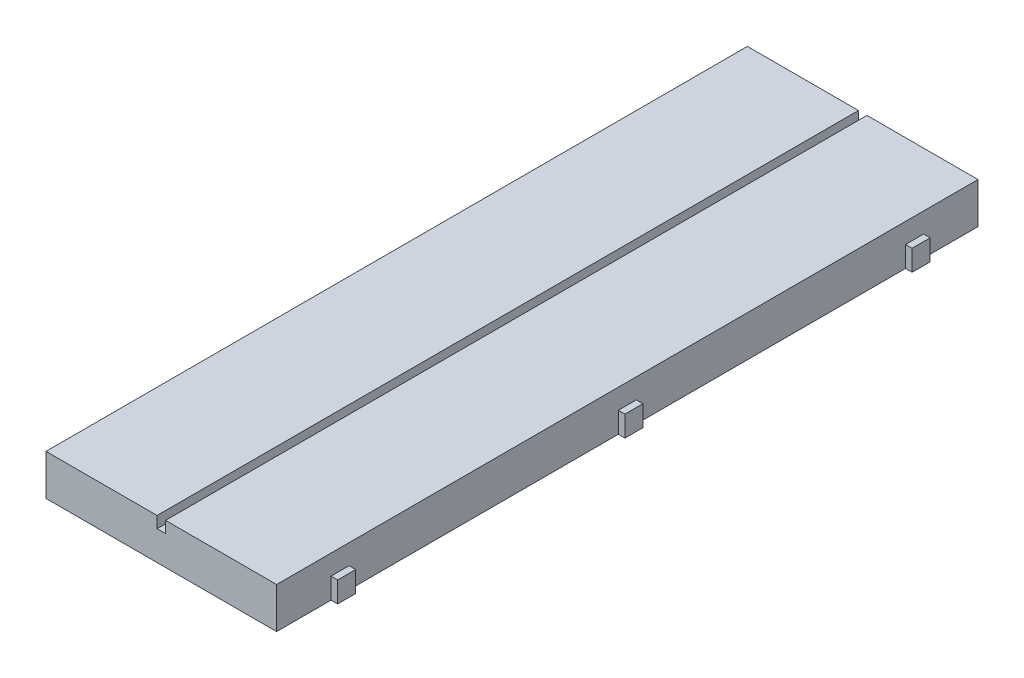
SolidWorks part; units mm, degrees
ref_plane "Front Plane" through (0, 0, 0) normal (0, 0, 1) x (1, 0, 0)
ref_plane "Top Plane" through (0, 0, 0) normal (0, 1, 0) x (1, 0, 0)
ref_plane "Right Plane" through (0, 0, 0) normal (1, 0, 0) x (0, 0, -1)
sketch "Sketch1" plane through (0, 0, 0) normal (0, 1, 0) x (1, 0, 0)
  line L1 (-27.125, -82.5) -> (27.125, -82.5)
  line L2 (-27.125, -82.5) -> (-27.125, 82.5)
  line L3 (-27.125, 82.5) -> (27.125, 82.5)
  line L4 (27.125, -82.5) -> (27.125, 82.5)
  line L5 (-27.125, -82.5) -> (27.125, 82.5) construction
  line L6 (-27.125, 82.5) -> (27.125, -82.5) construction
  point P0 (0, 0)
  dimension "D1" = 54.25
  dimension "D2" = 165
extrude "Boss-Extrude1" add sketch "Sketch1" against normal blind 9.6
sketch "Sketch2" plane through (27.125, 0, 0) normal (1, 0, 0) x (0, 0, -1)
  line L0 (82.5, -4.7) -> (69.7, -4.7)
  line L1 (82.5, -9.6) -> (82.5, 0) construction
  line L2 (-82.5, -9.6) -> (82.5, -9.6) construction
  line L3 (69.7, -4.7) -> (65.45, -4.7)
  line L4 (69.7, -4.7) -> (69.7, -9.6)
  line L5 (69.7, -9.6) -> (65.45, -9.6)
  line L6 (65.45, -4.7) -> (65.45, -9.6)
  line L7 (0, 0) -> (0, -9.6)
  line L8 (-2.125, -4.7) -> (2.125, -4.7)
  line L9 (-2.125, -4.7) -> (-2.125, -9.6)
  line L10 (-2.125, -9.6) -> (2.125, -9.6)
  line L11 (2.125, -4.7) -> (2.125, -9.6)
  line L12 (-2.125, -4.7) -> (2.125, -9.6) construction
  line L13 (-2.125, -9.6) -> (2.125, -4.7) construction
  line L14 (-69.7, -9.6) -> (-65.45, -9.6)
  line L15 (-65.45, -4.7) -> (-65.45, -9.6)
  line L16 (-69.7, -4.7) -> (-65.45, -4.7)
  line L17 (-69.7, -4.7) -> (-69.7, -9.6)
  line L18 (-69.7, -4.7) -> (-82.5, -4.8)
  line L19 (-82.5, -9.6) -> (-82.5, 0) construction
  point P9 (0, -7.15)
  line M14 (-82.5, -9.6) -> (82.5, -9.6)
  dimension "D1" = 12.8
  dimension "D2" = 4.9
  dimension "D3" = 4.25
  dimension "D4" = 4.25
  dimension "D5" = 4.9
  dimension "D6" = 12.8
extrude "Boss-Extrude2" add sketch "Sketch2" along normal blind 1.55 and the other way blind 1.55 contours L16 L17 L15 M14 | L3 L6 L4 M14 | L8 L11 L10 L9
sketch "Sketch15" plane through (-27.125, 0, 0) normal (-1, 0, 0) x (0, 0, 1)
  line L0 (82.5, -9.6) -> (82.5, 0) construction
  line L2 (-82.5, -9.6) -> (82.5, -9.6) construction
  line L3 (69.7, -4.7) -> (65.45, -4.7)
  line L4 (69.7, -4.7) -> (69.7, -9.6)
  line L5 (69.7, -9.6) -> (65.45, -9.6)
  line L6 (65.45, -4.7) -> (65.45, -9.6)
  line L7 (-69.7, -9.6) -> (-65.45, -9.6)
  line L8 (-65.45, -4.7) -> (-65.45, -9.6)
  line L9 (-69.7, -4.7) -> (-65.45, -4.7)
  line L10 (-2.125, -4.7) -> (2.125, -4.7)
  line L11 (-2.125, -4.7) -> (-2.125, -9.6)
  line L12 (-2.125, -9.6) -> (2.125, -9.6)
  line L13 (2.125, -4.7) -> (2.125, -9.6)
  line L14 (-2.125, -4.7) -> (2.125, -9.6) construction
  line L15 (-2.125, -9.6) -> (2.125, -4.7) construction
  line L16 (-69.7, -4.7) -> (-69.7, -9.6)
  point P3 (0, -4.7)
  point P9 (67.575, -7.15)
  point P12 (0, -4.7)
  dimension "D1" = 4.25
  dimension "D2" = 4.9
  dimension "D3" = 12.8
  dimension "D4" = 4.25
  dimension "D5" = 4.9
extrude "Cut-Extrude1" cut sketch "Sketch15" against normal blind 1.55
sketch "Sketch17" plane through (0, 0, 0) normal (0, 1, 0) x (1, 0, 0)
  line L0 (27.125, 82.5) -> (-27.125, 82.5) construction
  line L1 (-1, -82.5) -> (1, -82.5)
  line L2 (-1, -82.5) -> (-1, 82.5)
  line L3 (-1, 82.5) -> (1, 82.5)
  line L4 (1, -82.5) -> (1, 82.5)
  line L5 (-1, -82.5) -> (1, 82.5) construction
  line L6 (-1, 82.5) -> (1, -82.5) construction
  point P0 (0, 0)
  dimension "D1" = 2
extrude "Cut-Extrude2" cut sketch "Sketch17" against normal blind 2.7
